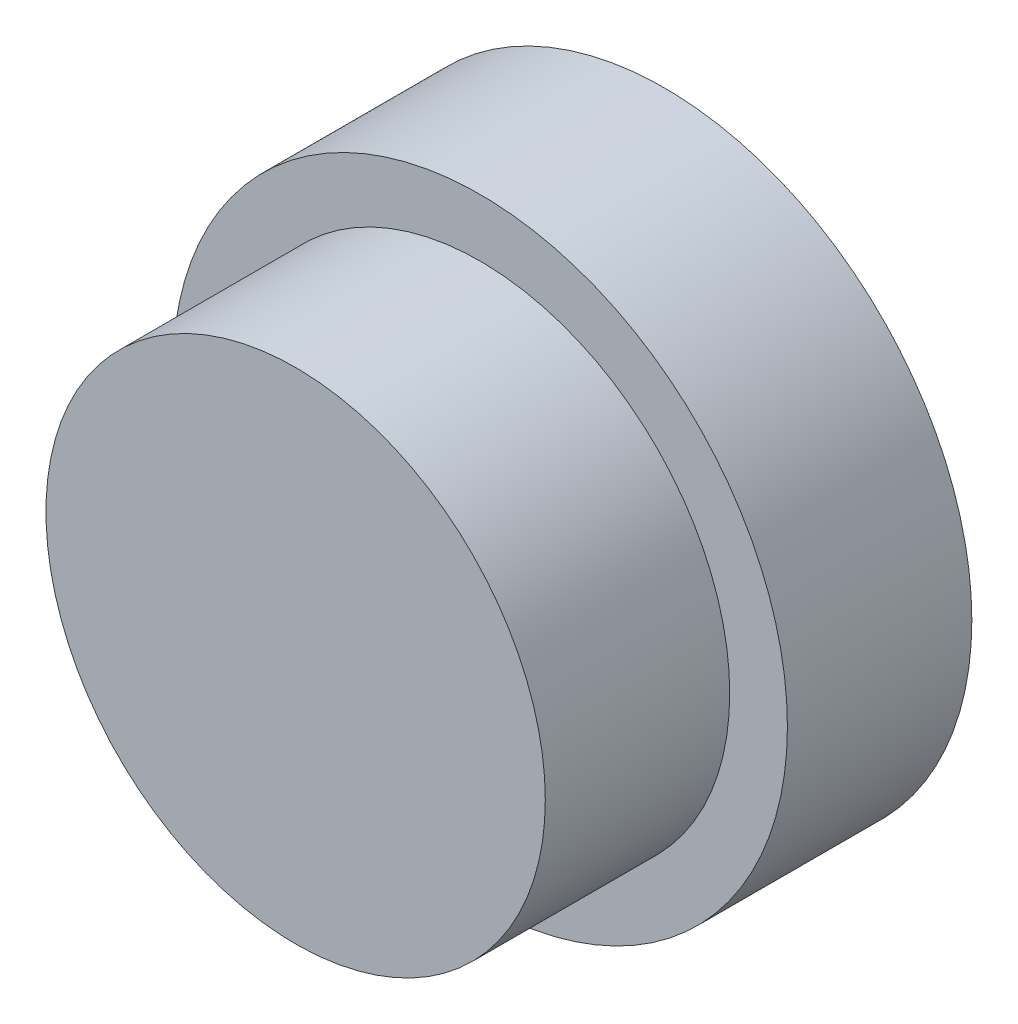
SolidWorks part; units mm, degrees
ref_plane "Front Plane" through (0, 0, 0) normal (0, 0, 1) x (1, 0, 0)
ref_plane "Top Plane" through (0, 0, 0) normal (0, 1, 0) x (1, 0, 0)
ref_plane "Right Plane" through (0, 0, 0) normal (1, 0, 0) x (0, 0, -1)
sketch "Sketch1" plane through (0, 0, 0) normal (0, 0, 1) x (1, 0, 0)
  circle A0 centre (0, 0) radius 5
  dimension "D1" = 10
extrude "Boss-Extrude1" add sketch "Sketch1" along normal blind 3
sketch "Sketch2" plane through (0, 0, 3) normal (0, 0, 1) x (1, 0, 0)
  circle A0 centre (0, 0) radius 4.0614
extrude "Boss-Extrude2" add sketch "Sketch2" along normal blind 3
